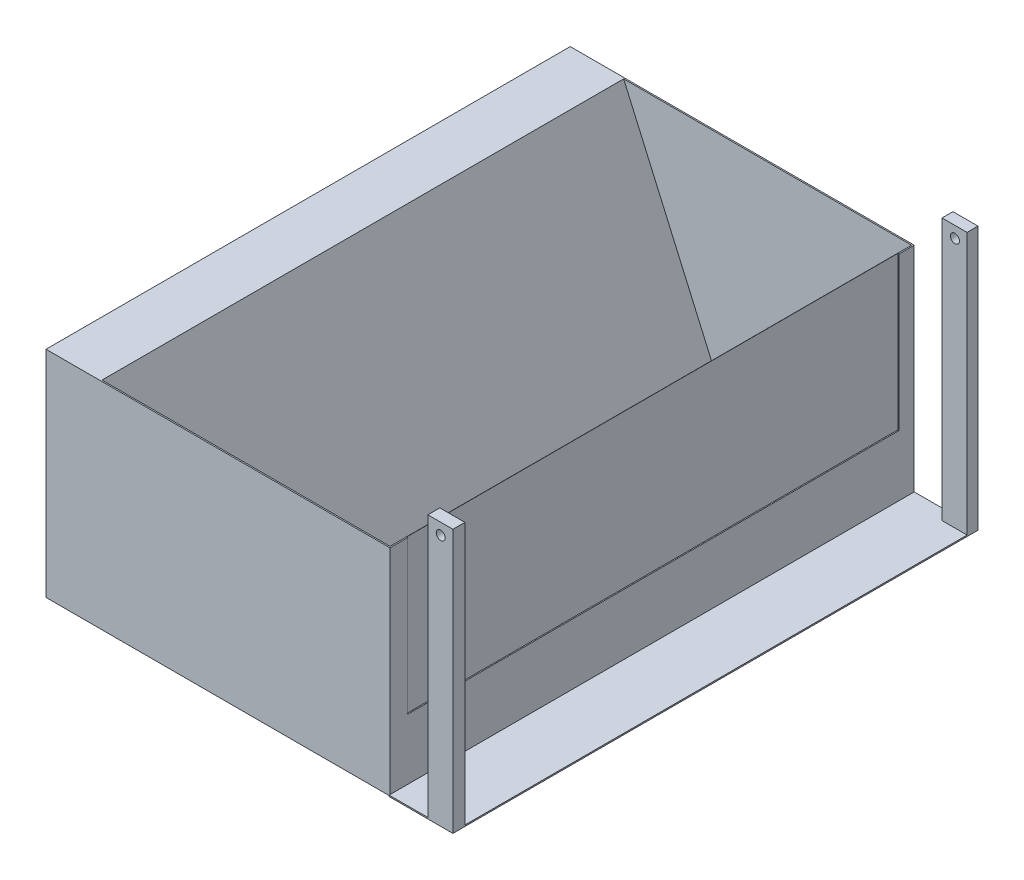
SolidWorks part; units mm, degrees
ref_plane "Front Plane" through (0, 0, 0) normal (0, 0, 1) x (1, 0, 0)
ref_plane "Top Plane" through (0, 0, 0) normal (0, 1, 0) x (1, 0, 0)
ref_plane "Right Plane" through (0, 0, 0) normal (1, 0, 0) x (0, 0, -1)
sketch "Sketch1" plane through (0, 0, 0) normal (0, 1, 0) x (1, 0, 0)
  line L2 (17.0836, -25.8179) -> (-782.9164, -25.8179)
  line L3 (17.0836, -25.8179) -> (17.0836, 1193.3821)
  line L4 (17.0836, 1193.3821) -> (-782.9164, 1193.3821)
  line L5 (-782.9164, -25.8179) -> (-782.9164, 1193.3821)
  dimension "D1" = 1219.2
  dimension "D2" = 800
extrude "Boss-Extrude1" add sketch "Sketch1" along normal blind 500 contours L4 L5 L2 L3
shell "Shell1" thickness 3
sketch "Sketch5" plane through (17.0836, 0, 0) normal (1, 0, 0) x (0, 0, -1)
  line L0 (-25.8179, 500) -> (1193.3821, 500) construction
  line L1 (15.3569, 500) -> (1158.3569, 500)
  line L2 (15.3569, 500) -> (15.3569, 144.4)
  line L3 (15.3569, 144.4) -> (1158.3569, 144.4)
  line L4 (1158.3569, 500) -> (1158.3569, 144.4)
  dimension "D1" = 355.6
  dimension "D2" = 1143
extrude "Cut-Extrude2" cut sketch "Sketch5" against normal blind 2.54
sketch "Sketch6" plane through (0, 0, 25.8179) normal (0, 0, 1) x (1, 0, 0)
  line L1 (17.0836, 0) -> (-782.9164, 0) construction
  line L2 (-436.2987, 0) -> (-782.9164, 0)
  line L3 (-782.9164, 0) -> (-782.9164, 500)
  line L4 (-436.2987, 0) -> (-655.7345, 500)
  line L5 (17.0836, 500) -> (-782.9164, 500) construction
  line L7 (-782.9164, 500) -> (-655.7345, 500)
extrude "Boss-Extrude3" add sketch "Sketch6" against normal blind 1219.2
sketch "Sketch7" plane through (0, 3, 0) normal (0, 1, 0) x (1, 0, 0)
  line L1 (17.0836, 1193.3821) -> (165.4153, 1193.3821)
  line L2 (17.0836, 1193.3821) -> (17.0836, -27.8405)
  line L3 (17.0836, -27.8405) -> (165.4153, -27.8405)
  line L4 (165.4153, 1193.3821) -> (165.4153, -27.8405)
extrude "Boss-Extrude4" add sketch "Sketch7" along normal blind 0.0001 and the other way blind 3.048 separate body contours L2 L1 L4 L3
sketch "Sketch8" plane through (0, 3.0001, 0) normal (0, 1, 0) x (1, 0, 0)
  line L0 (17.0836, 1193.3821) -> (165.4153, 1193.3821) construction
  line L1 (107.1863, 1193.3821) -> (165.4153, 1193.3821)
  line L2 (107.1863, 1193.3821) -> (107.1863, 1167.9821)
  line L3 (107.1863, 1167.9821) -> (165.4153, 1167.9821)
  line L4 (165.4153, 1193.3821) -> (165.4153, 1167.9821)
  line L5 (165.4153, 1193.3821) -> (165.4153, -27.8405) construction
  line L7 (165.4153, -27.8405) -> (107.1863, -27.8405)
  line L8 (165.4153, -27.8405) -> (165.4153, 0)
  line L9 (165.4153, 0) -> (107.1863, 0)
  line L10 (107.1863, -27.8405) -> (107.1863, 0)
  dimension "D1" = 25.4
extrude "Boss-Extrude5" add sketch "Sketch8" along normal blind 609.6
sketch "Sketch9" plane through (0, 0, 27.8405) normal (0, 0, 1) x (1, 0, 0)
  circle A0 centre (137.0964, 586.2156) radius 10.4501
extrude "Cut-Extrude3" cut sketch "Sketch9" against normal blind 1219.2
